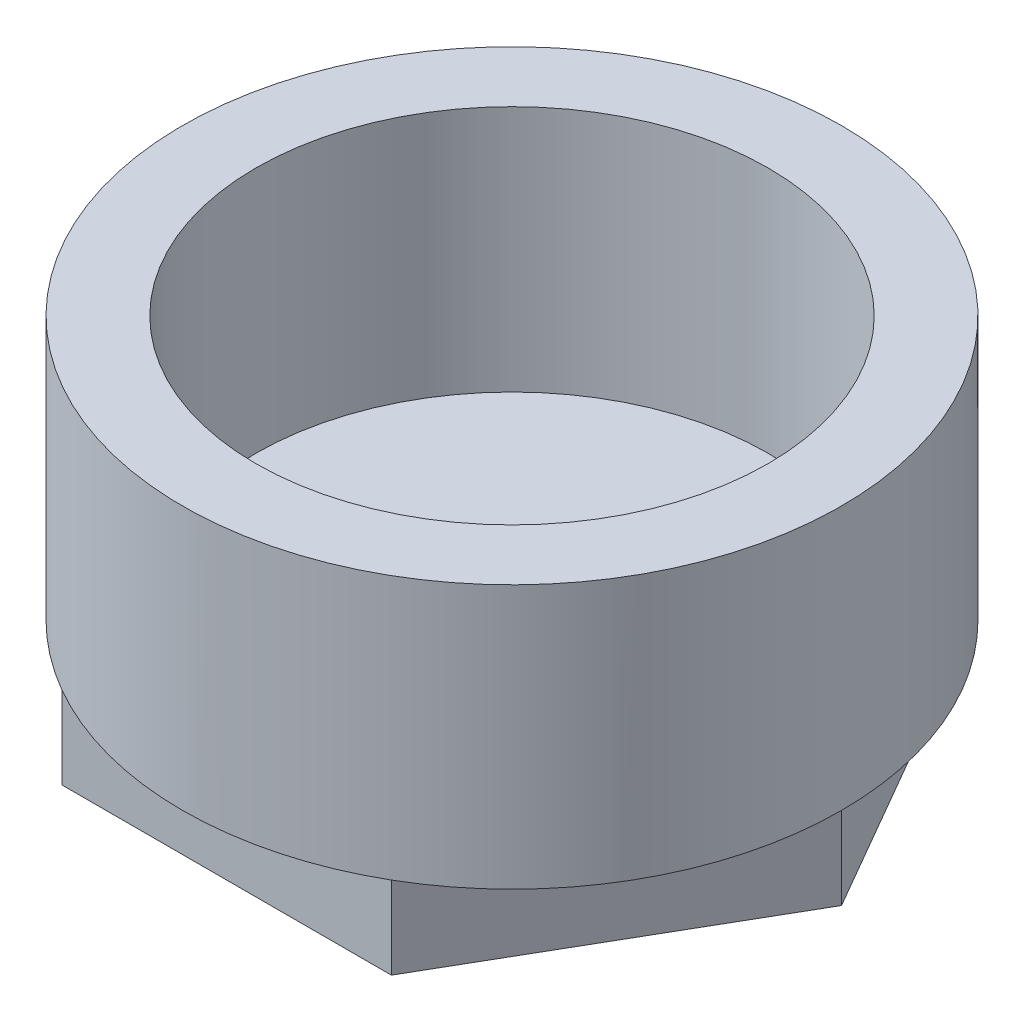
SolidWorks part; units mm, degrees
material "1.0035 (S185)"
ref_plane "Piano frontale" through (0, 0, 0) normal (0, 0, 1) x (1, 0, 0)
ref_plane "Piano superiore" through (0, 0, 0) normal (0, 1, 0) x (1, 0, 0)
ref_plane "Piano destro" through (0, 0, 0) normal (1, 0, 0) x (0, 0, -1)
sketch "Schizzo1" plane through (0, 0, 0) normal (0, 0, 1) x (1, 0, 0)
  line L0 (0, 0) -> (-20, 0)
  line L1 (-20, 0) -> (-20, 21)
  line L2 (-20, 21) -> (-15.5465, 21)
  line L3 (-15.5465, 21) -> (-15.5465, 6)
  line L4 (-15.5465, 6) -> (0, 6)
  line L5 (0, 6) -> (0, 0)
  line L6 (0, 0) -> (0, 10.8439) construction
  dimension "D1" = 40
  dimension "D2" = 31.093
  dimension "D3" = 15
  dimension "D4" = 21
revolve "Rivoluzione1" add sketch "Schizzo1" angle 360 about L6
sketch "Schizzo2" plane through (0, 0, 0) normal (0, -1, 0) x (1, 0, 0)
  line L1 (0, 0) -> (10, 0) construction
  circle A0 centre (0, 0) radius 3.175
  circle A1 centre (10, 0) radius 0.5
  dimension "D1" = 6.35
  dimension "D2" = 1
  dimension "D3" = 10
extrude "Taglio-Estrusione1" cut sketch "Schizzo2" against normal blind 10
sketch "Schizzo3" plane through (0, 0, 0) normal (0, -1, 0) x (1, 0, 0)
  circle A0 centre (0, 0) radius 1.019
  circle A1 centre (0, 0) radius 1.5875
  dimension "D1" = 3.175
extrude "Estrusione-Estrusione1" [suppressed] add sketch "Schizzo3" along normal blind 8
sketch "Schizzo4" plane through (0, 0, 0) normal (0, 0, 1) x (1, 0, 0)
  line L0 (0, 0) -> (0, -9.8437)
sketch "Schizzo5" plane through (0, 0, 0) normal (0, -1, 0) x (-1, 0, 0)
  line L0 (10, 17.3205) -> (20, 0)
  line L1 (20, 0) -> (10, -17.3205)
  line L2 (10, -17.3205) -> (-10, -17.3205)
  line L3 (-10, -17.3205) -> (-20, 0)
  line L4 (-20, 0) -> (-10, 17.3205)
  line L5 (-10, 17.3205) -> (10, 17.3205)
  line L6 (-8.5, 0) -> (0, 0) construction
  circle A0 centre (0, 0) radius 20 construction
  circle A1 centre (0, 0) radius 15
  circle A2 centre (-8.5, 0) radius 0.5
  circle M9 centre (0, 0) radius 20
  dimension "D1" = 1
  dimension "D2" = 8.5
extrude "Taglio-Estrusione2" cut sketch "Schizzo5" against normal blind 5 contours L5 M9 | L0 M9 | L1 M9 | L2 M9 | L3 M9 | L4 M9
